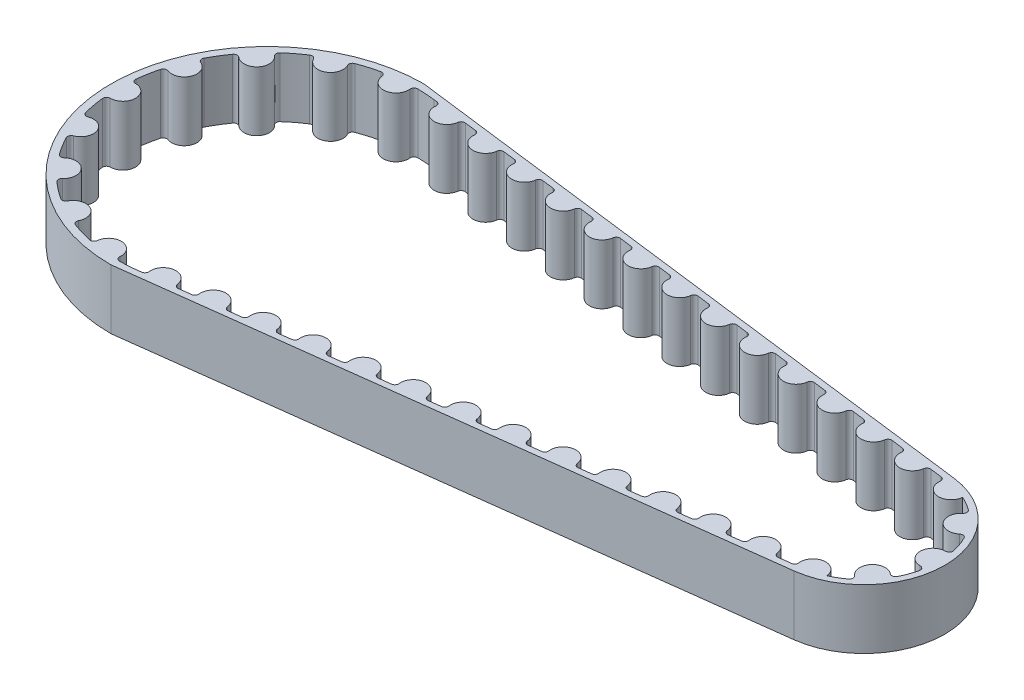
SolidWorks part; units mm, degrees
material "EPDM 60 硬度计"
ref_plane "前视基准面" through (0, 0, 0) normal (0, 0, 1) x (1, 0, 0)
ref_plane "上视基准面" through (0, 0, 0) normal (0, 1, 0) x (1, 0, 0)
ref_plane "右视基准面" through (0, 0, 0) normal (1, 0, 0) x (0, 0, -1)
sketch "草图1" plane through (0, 0, 0) normal (0, 1, 0) x (1, 0, 0)
  line L0 (2.5, 19.8431) -> (81.25, 9.9216)
  line L1 (0, 0) -> (2.063, 0) construction
  line L2 (101.0302, 0) -> (0, 0) construction
  line L3 (2.5, -19.8431) -> (81.25, -9.9216)
  line L4 (0, 23.5728) -> (0, -28.333) construction
  line L5 (15.1869, 25.5397) -> (13.9934, 16.067) construction
  line L6 (10.4043, 18.3433) -> (24.9263, 16.5137) construction
  line L7 (0, 21) -> (81.3544, 10.7443)
  line L8 (0, -21) -> (81.3544, -10.7443)
  arc A0 (2.5, 19.8431) -> (2.5, -19.8431) centre (0, 0) ccw
  arc A1 (81.25, -9.9216) -> (81.25, 9.9216) centre (80, 0) ccw
  arc A5 (0, -21) -> (0, 21) centre (0, 0) cw
  arc A6 (81.3544, -10.7443) -> (81.3544, 10.7443) centre (80, 0) ccw
  dimension "D2" = 10
  dimension "D3" = 80
  dimension "D1" = 20
extrude "凸台-拉伸1" add sketch "草图1" along normal blind 8
sketch "草图2" plane through (0, 0, 0) normal (0, 1, 0) x (1, 0, 0)
  line L0 (41.7051, 21.9742) -> (39.7415, 6.3881) construction
  line L1 (37.4441, 14.9366) -> (46.2306, 13.8296) construction
  line L3 (38.6455, 15.2892) -> (43.011, 14.7392)
  arc A0 (39.0791, 14.7306) -> (42.4524, 14.3056) centre (40.7658, 14.5181) ccw
  arc A1 (43.011, 14.7392) -> (42.4524, 14.3056) centre (42.9485, 14.2431) ccw
  arc A2 (38.6455, 15.2892) -> (39.0791, 14.7306) centre (38.583, 14.7931) cw
  dimension "D1" = 1.7
  dimension "D2" = 0.5
extrude "凸台-拉伸2" add sketch "草图2" along normal blind 8
pattern_linear "阵列(线性)2" count 8 spacing 6 along (0.9922, 0, 0.125) of "凸台-拉伸2"
pattern_linear "阵列(线性)3" count 7 spacing 6 along (-0.9922, 0, -0.125) of "凸台-拉伸2"
mirror "镜向6" about plane through (0, 0, 0) normal (0, 0, 1) of "阵列(线性)3", "凸台-拉伸2"
mirror "镜向7" about plane through (0, 0, 0) normal (0, 0, 1) of "阵列(线性)2"
sketch "草图3" plane through (0, 0, 0) normal (0, 1, 0) x (1, 0, 0)
  line L0 (-24.5411, 0) -> (-14.2099, 0) construction
  line L1 (-4.4, 0) -> (4.4, 0) construction
  line L2 (-19.3755, 3.4588) -> (-19.3755, -4.5204) construction
  arc A0 (-19.3755, -1.7) -> (-19.3755, 1.7) centre (-19.3755, 0) ccw
  arc A1 (-19.8723, 2.2564) -> (-19.3755, 1.7) centre (-19.3755, 2.2) ccw
  arc A2 (2.5, 19.8431) -> (2.5, -19.8431) centre (0, 0) ccw construction
  arc A3 (-19.8723, 2.2564) -> (-19.8723, -2.2564) centre (0, 0) ccw
  arc A4 (-19.8723, -2.2564) -> (-19.3755, -1.7) centre (-19.3755, -2.2) cw
  dimension "D1" = 0.5
  dimension "D2" = 1.7
extrude "凸台-拉伸4" add sketch "草图3" along normal blind 8
pattern_circular "阵列(圆周)1" count 5 every 21 about axis through (0, 0, 0) along (0, 1, 0) of "凸台-拉伸4"
mirror "镜向8" about plane through (0, 0, 0) normal (0, 0, 1) of "阵列(圆周)1"
sketch "草图4" plane through (0, 0, 0) normal (0, 1, 0) x (1, 0, 0)
  line L0 (85.7349, 0) -> (92.6515, 0) construction
  line L1 (-4.4, 0) -> (4.4, 0) construction
  line L2 (89.2418, 2.7414) -> (89.2418, -2.9876) construction
  arc A0 (89.2418, 1.7) -> (89.2418, -1.7) centre (89.2418, 0) ccw
  arc A1 (89.7282, 2.3158) -> (89.2418, 1.7) centre (89.2418, 2.2) cw
  arc A2 (84.1321, -9.1064) -> (84.1321, 9.1064) centre (80, 0) ccw construction
  arc A3 (89.7282, -2.3158) -> (89.7282, 2.3158) centre (80, 0) ccw
  arc A4 (89.7282, -2.3158) -> (89.2418, -1.7) centre (89.2418, -2.2) ccw
  dimension "D1" = 0.5
  dimension "D2" = 1.7
extrude "凸台-拉伸5" add sketch "草图4" along normal blind 8
pattern_circular "阵列(圆周)2" count 2 every 40 about axis through (80, 0, 0) along (0, 1, 0) of "凸台-拉伸5"
mirror "镜向9" about plane through (0, 0, 0) normal (0, 0, 1) of "阵列(圆周)2"
